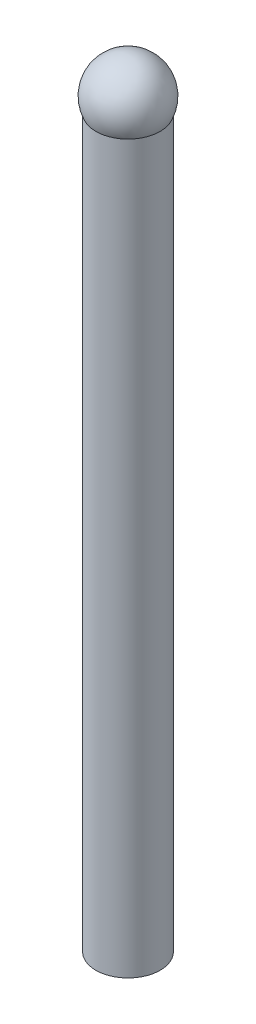
SolidWorks part; units mm, degrees
ref_plane "Спереди" through (0, 0, 0) normal (0, 0, 1) x (1, 0, 0)
ref_plane "Сверху" through (0, 0, 0) normal (0, 1, 0) x (1, 0, 0)
ref_plane "Справа" through (0, 0, 0) normal (1, 0, 0) x (0, 0, -1)
sketch "Эскиз1" plane through (0, 0, 0) normal (0, 1, 0) x (1, 0, 0)
  circle A0 centre (0, 0) radius 0.65
extrude "Бобышка-Вытянуть1" add sketch "Эскиз1" along normal blind 15
sketch "Эскиз3" plane through (0, 0, 0) normal (0, 0, 1) x (1, 0, 0)
  line L0 (0, 0) -> (0, 15.0009) construction
  line L1 (0.7154, 15.0009) -> (0.65, 15) construction
  line L2 (0.65, 15) -> (0.65, 14.702) construction
  line L3 (0.65, 0) -> (0.65, 15) construction
  line L4 (0.65, 14.702) -> (-0.65, 14.702) construction
  line L5 (-0.65, 14.702) -> (-0.65, 15) construction
  line L6 (-0.65, 15) -> (-0.7154, 15.0009) construction
  line L7 (0.7154, 15.0009) -> (-0.7154, 15.0009)
  circle A0 centre (0, 15.0009) radius 0.7154
revolve "Повернуть23" add sketch "Эскиз3" angle 360 about L7
